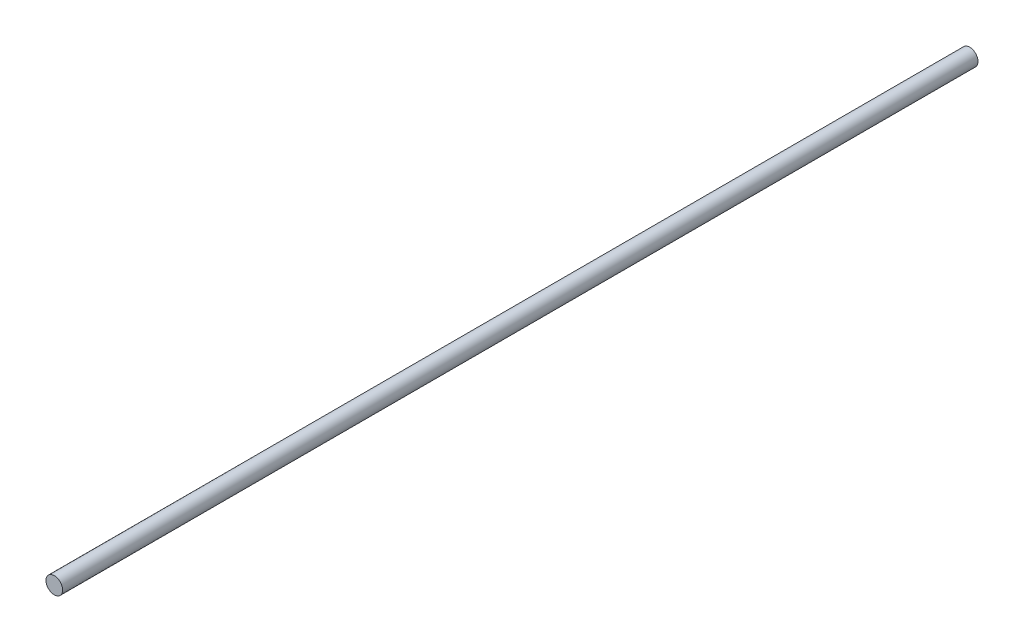
SolidWorks part; units mm, degrees
material "AISI 1020 Steel, Cold Rolled"
ref_plane "Front Plane" through (0, 0, 0) normal (0, 0, 1) x (1, 0, 0)
ref_plane "Top Plane" through (0, 0, 0) normal (0, 1, 0) x (1, 0, 0)
ref_plane "Right Plane" through (0, 0, 0) normal (1, 0, 0) x (0, 0, -1)
sketch "Sketch1" plane through (0, 0, 0) normal (0, 0, 1) x (1, 0, 0)
  circle A0 centre (0, 0) radius 8
  dimension "D1" = 16
extrude "Boss-Extrude1" add sketch "Sketch1" along normal blind 880
ref_plane "Plane1" through (0, -8, 0) normal (0, 1, 0) x (-1, 0, 0)
sketch "Sketch4" plane through (0, -8, 0) normal (0, 1, 0) x (-1, 0, 0)
  circle A0 centre (0, 100) radius 2.1
  dimension "D2" = 4.2
  dimension "D1" = 100
extrude "Cut-Extrude2" cut sketch "Sketch4" along normal blind 12.4
sketch "Sketch6" plane through (0, -8, 0) normal (0, 1, 0) x (-1, 0, 0)
  line L0 (0, 0) -> (0, 100) construction
pattern_linear "LPattern1" count 5 spacing 150 along (0, 0, 1) of "Cut-Extrude2"
